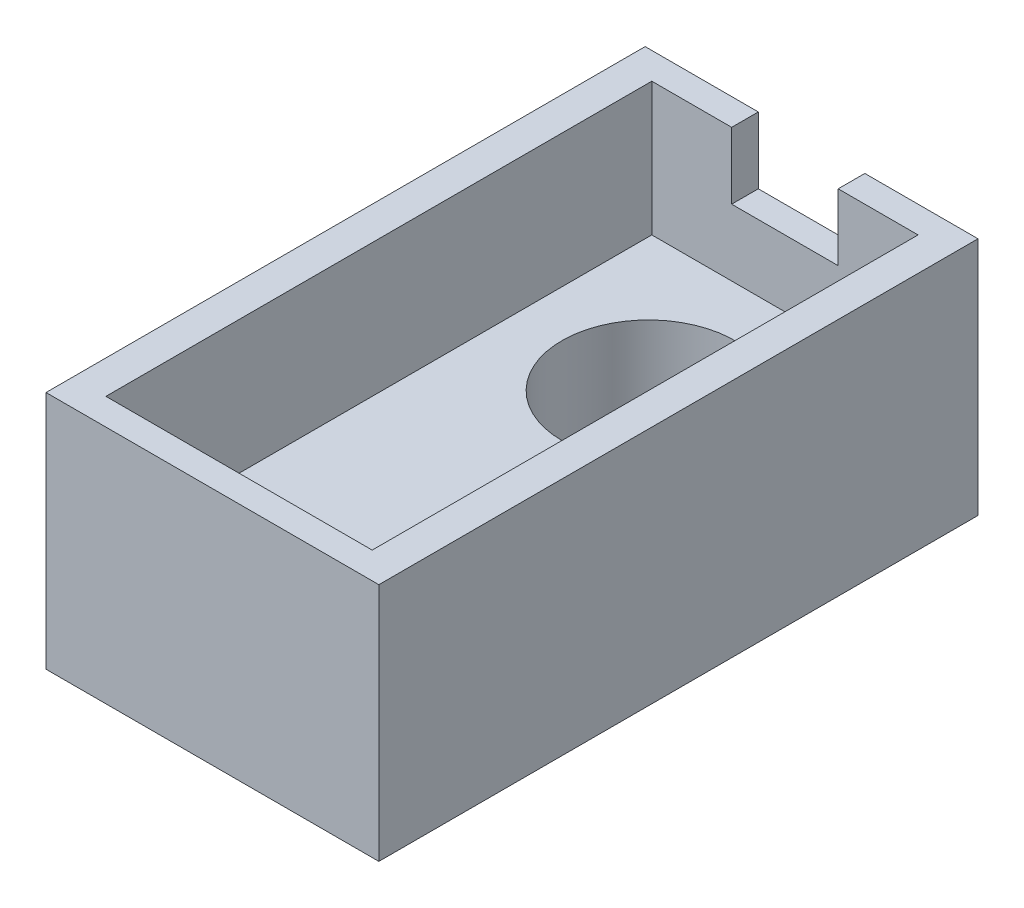
SolidWorks part; units mm, degrees
ref_plane "Front Plane" through (0, 0, 0) normal (0, 0, 1) x (1, 0, 0)
ref_plane "Top Plane" through (0, 0, 0) normal (0, 1, 0) x (1, 0, 0)
ref_plane "Right Plane" through (0, 0, 0) normal (1, 0, 0) x (0, 0, -1)
sketch "Sketch1" plane through (0, 0, 0) normal (0, 1, 0) x (1, 0, 0)
  line L1 (0, 0) -> (25, 0)
  line L2 (0, 0) -> (0, 45)
  line L3 (0, 45) -> (25, 45)
  line L4 (25, 0) -> (25, 45)
  dimension "D2" = 25
  dimension "D3" = 45
extrude "Base" add sketch "Sketch1" along normal blind 13
sketch "Sketch2" plane through (0, 13, 0) normal (0, 1, 0) x (1, 0, 0)
  line L0 (25, 0) -> (25, 45) construction
  line L1 (2.5, 2) -> (22.5, 2)
  line L2 (2.5, 2) -> (2.5, 43)
  line L3 (2.5, 43) -> (22.5, 43)
  line L4 (22.5, 2) -> (22.5, 43)
  line L5 (25, 45) -> (0, 45) construction
  point P6 (22.5, 22.5)
  point P7 (25, 22.5)
  point P11 (12.5, 43)
  point P12 (12.5, 45)
  dimension "D1" = 41
  dimension "D2" = 20
extrude "Seat" cut sketch "Sketch2" against normal blind 5
sketch "Sketch3" plane through (0, 8, 0) normal (0, 1, 0) x (1, 0, 0)
  line L1 (22.5, 43) -> (2.5, 43) construction
  circle A0 centre (12.5, 32.75) radius 1.5
  point P8 (12.5, 43)
  dimension "D1" = 3
  dimension "D3" = 10.25
extrude "ScrewHole" cut sketch "Sketch3" against normal up to surface (8 mm away) up to face at (12.5, 0, -22.5)
sketch "Sketch4" plane through (0, 8, 0) normal (0, 1, 0) x (1, 0, 0)
  circle A0 centre (12.5, 32.75) radius 6.5
  circle A1 centre (12.5, 32.75) radius 1.5 construction
  dimension "D1" = 13
extrude "ScrewInset" cut sketch "Sketch4" against normal blind 7
sketch "Sketch6" plane through (0, 13, 0) normal (0, 1, 0) x (1, 0, 0)
  line L1 (2.5, 43) -> (2.5, 2)
  line L9 (22.5, 2) -> (22.5, 43)
  line L10 (2.5, 2) -> (22.5, 2)
  line L12 (0, 45) -> (0, 0)
  line L13 (0, 0) -> (25, 0)
  line L14 (25, 45) -> (25, 0)
  line L15 (22.5, 43) -> (16.5, 43)
  line L16 (22.5, 43) -> (2.5, 43) construction
  line L17 (16.5, 43) -> (16.5, 45)
  line L18 (25, 45) -> (0, 45) construction
  line L20 (8.5, 45) -> (8.5, 43)
  line L21 (8.5, 43) -> (2.5, 43)
  line L22 (25, 45) -> (16.5, 45)
  line L23 (8.5, 45) -> (0, 45)
  point P4 (12.5, 45)
  dimension "D1" = 4
  dimension "D2" = 8
extrude "SeatSecurity" add sketch "Sketch6" along normal blind 5
